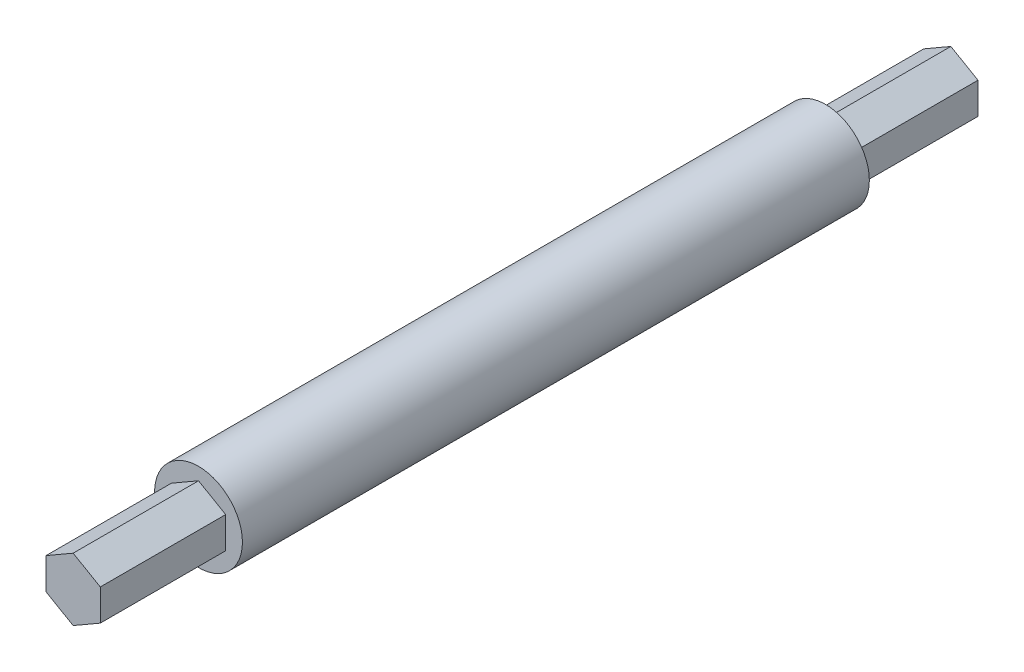
SolidWorks part; units mm, degrees
ref_plane "Front Plane" through (0, 0, 0) normal (0, 0, 1) x (1, 0, 0)
ref_plane "Top Plane" through (0, 0, 0) normal (0, 1, 0) x (1, 0, 0)
ref_plane "Right Plane" through (0, 0, 0) normal (1, 0, 0) x (0, 0, -1)
sketch "Sketch1" plane through (0, 0, 0) normal (0, 0, 1) x (1, 0, 0)
  circle A0 centre (0, 0) radius 7
  dimension "D1" = 14
extrude "Boss-Extrude1" add sketch "Sketch1" against normal blind 100
sketch "Sketch2" plane through (0, 0, 0) normal (0, 0, 1) x (1, 0, 0)
  line L1 (0, 5) -> (-4.3301, 2.5)
  line L2 (-4.3301, 2.5) -> (-4.3301, -2.5)
  line L3 (-4.3301, -2.5) -> (0, -5)
  line L4 (0, -5) -> (4.3301, -2.5)
  line L5 (4.3301, -2.5) -> (4.3301, 2.5)
  line L6 (4.3301, 2.5) -> (0, 5)
  circle A0 centre (0, 0) radius 5 construction
  circle A1 centre (0, 0) radius 4.3301 construction
  circle A2 centre (0, 0) radius 7 construction
  dimension "D1" = 10
  dimension "D2" = 5
  dimension "D3" = 2.5
extrude "Boss-Extrude2" add sketch "Sketch2" along normal blind 20
sketch "Sketch3" plane through (0, 0, -100) normal (0, 0, -1) x (-1, 0, 0)
  line L1 (0, 5) -> (-4.3301, 2.5)
  line L2 (-4.3301, 2.5) -> (-4.3301, -2.5)
  line L3 (-4.3301, -2.5) -> (0, -5)
  line L4 (0, -5) -> (4.3301, -2.5)
  line L5 (4.3301, -2.5) -> (4.3301, 2.5)
  line L6 (4.3301, 2.5) -> (0, 5)
  circle A1 centre (0, 0) radius 5 construction
  circle A2 centre (0, 0) radius 4.3301 construction
  dimension "D1" = 5
  dimension "D2" = 2.5
extrude "Boss-Extrude3" add sketch "Sketch3" along normal blind 20
